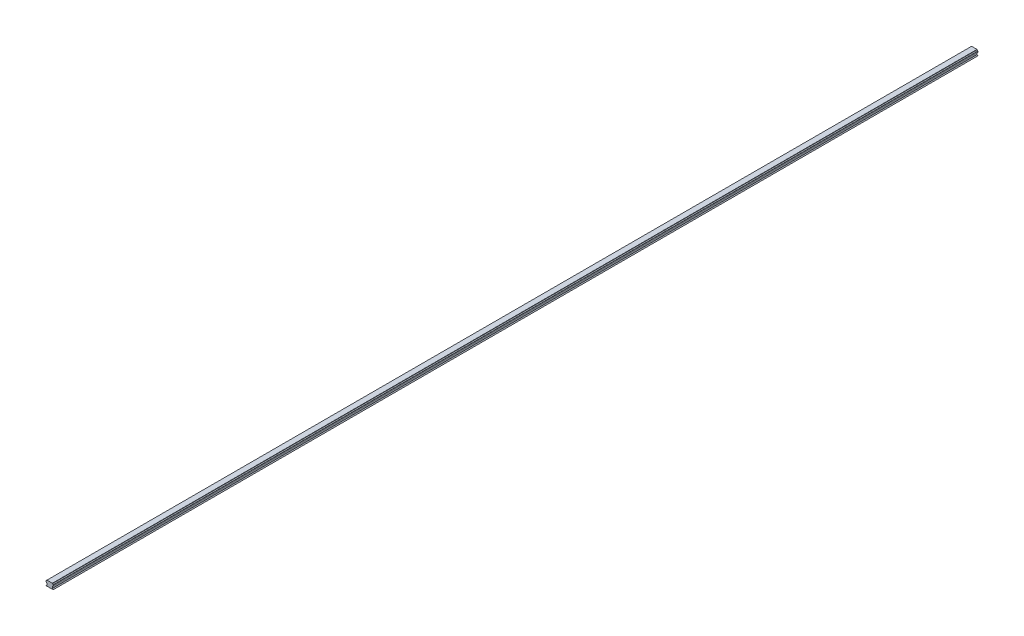
SolidWorks part; units mm, degrees
ref_plane "Piano frontale" through (0, 0, 0) normal (0, 0, 1) x (1, 0, 0)
ref_plane "Piano superiore" through (0, 0, 0) normal (0, 1, 0) x (1, 0, 0)
ref_plane "Piano destro" through (0, 0, 0) normal (1, 0, 0) x (0, 0, -1)
sketch "Schizzo1" plane through (0, 0, 0) normal (0, 0, 1) x (1, 0, 0)
  line L0 (-10.0012, -16.2762) -> (-7.5012, -13.7762)
  line L1 (-7.5012, -13.7762) -> (-7.5012, -8.7762)
  line L2 (-7.5012, -8.7762) -> (-8.0088, -8.2686)
  line L3 (-10.3066, -5.9708) -> (-10.5012, -5.7762)
  line L4 (-10.5012, -5.7762) -> (-10.5012, -2.7762)
  line L5 (-10.5012, -2.7762) -> (-10.3066, -2.5816)
  line L6 (-8.0088, -0.2838) -> (-7.5012, 0.2238)
  line L7 (-7.5012, 0.2238) -> (9.4988, 0.2238)
  line L8 (9.4988, 0.2238) -> (10.0064, -0.2838)
  line L9 (12.3042, -2.5816) -> (12.4988, -2.7762)
  line L10 (12.4988, -2.7762) -> (12.4988, -5.7762)
  line L11 (12.4988, -5.7762) -> (12.3042, -5.9708)
  line L12 (10.0064, -8.2686) -> (9.4988, -8.7762)
  line L13 (9.4988, -8.7762) -> (9.4988, -13.7762)
  line L14 (9.4988, -13.7762) -> (11.9988, -16.2762)
  line L15 (-10.0012, -16.2762) -> (11.9988, -16.2762)
  line L16 (11.9988, -16.2762) -> (12.5278, -16.8429)
  arc A0 (-8.0088, -8.2686) -> (-10.3066, -5.9708) centre (-10.5012, -8.4632) ccw
  arc A1 (-10.3066, -2.5816) -> (-8.0088, -0.2838) centre (-10.5012, -0.0892) ccw
  arc A2 (10.0064, -0.2838) -> (12.3042, -2.5816) centre (12.4988, -0.0892) ccw
  arc A3 (12.3042, -5.9708) -> (10.0064, -8.2686) centre (12.4988, -8.4632) ccw
extrude "Estrusione-Estrusione1" add sketch "Schizzo1" along normal blind 2900 contours A3 L11 L10 L9 A2 L8 L7 L6 A1 L5 L4 L3 A0 L2 L1 L0 L15 L14 L13 L12
